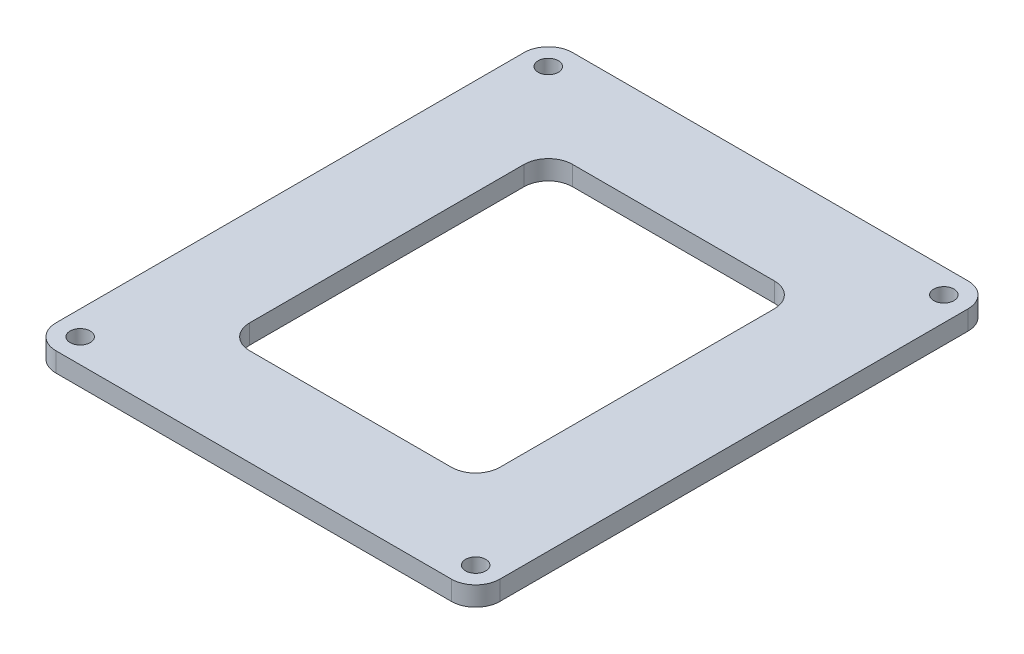
SolidWorks part; units mm, degrees
ref_plane "前视基准面" through (0, 0, 0) normal (0, 0, 1) x (1, 0, 0)
ref_plane "上视基准面" through (0, 0, 0) normal (0, 1, 0) x (1, 0, 0)
ref_plane "右视基准面" through (0, 0, 0) normal (1, 0, 0) x (0, 0, -1)
other "Configuration Table"
sketch "草图1" plane through (0, 0, 0) normal (0, 1, 0) x (1, 0, 0)
  line L0 (0, 46.8686) -> (0, -37.1951) construction
  line L1 (-27.5, -32) -> (27.5, -32)
  line L2 (-27.5, -32) -> (-27.5, 32)
  line L3 (-27.5, 32) -> (27.5, 32)
  line L4 (27.5, -32) -> (27.5, 32)
  line L5 (-27.5, -32) -> (27.5, 32) construction
  line L6 (-27.5, 32) -> (27.5, -32) construction
  line L7 (-32.226, 0) -> (32.7537, 0) construction
  line L8 (-15.5, -20) -> (-15.5, 20)
  line L9 (-15.5, 20) -> (15.5, 20)
  line L10 (15.5, -20) -> (15.5, 20)
  line L11 (-15.5, -20) -> (15.5, -20)
  circle A0 centre (-24.5, 29) radius 1.25
  circle A1 centre (24.5, 29) radius 1.25
  circle A2 centre (24.5, -29) radius 1.25
  circle A3 centre (-24.5, -29) radius 1.25
  point P0 (0, 0)
  dimension "D3" = 2.5
  dimension "D4" = 49
  dimension "D5" = 58
  dimension "D1" = 55
  dimension "D2" = 64
  dimension "D6" = 12
extrude "凸台-拉伸1" add sketch "草图1" along normal blind 2.4
fillet "圆角1" radius 3 8 edges at (-27.5, 1.2, -32) (27.5, 1.2, -32) (27.5, 1.2, 32) (-27.5, 1.2, 32) (-15.5, 1.2, 20) (15.5, 1.2, 20) (15.5, 1.2, -20) (-15.5, 1.2, -20)
